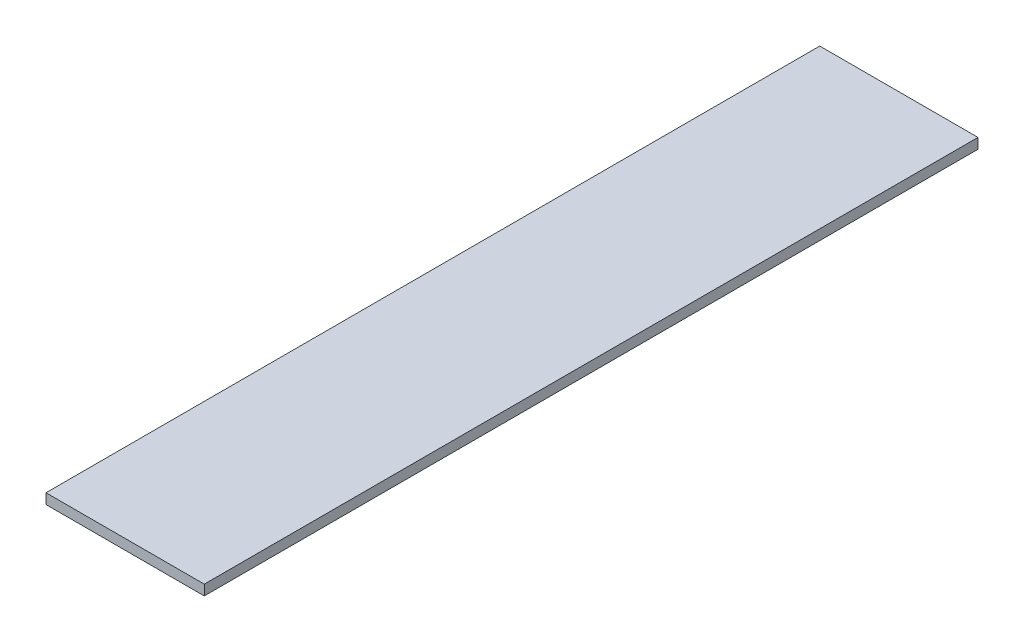
SolidWorks part; units mm, degrees
material "Pine"
ref_plane "Front Plane" through (0, 0, 0) normal (0, 0, 1) x (1, 0, 0)
ref_plane "Top Plane" through (0, 0, 0) normal (0, 1, 0) x (1, 0, 0)
ref_plane "Right Plane" through (0, 0, 0) normal (1, 0, 0) x (0, 0, -1)
sketch "Sketch1" plane through (0, 0, 0) normal (0, 1, 0) x (1, 0, 0)
  line L1 (-42.8625, 209.55) -> (42.8625, 209.55)
  line L2 (-42.8625, 209.55) -> (-42.8625, -209.55)
  line L3 (-42.8625, -209.55) -> (42.8625, -209.55)
  line L4 (42.8625, 209.55) -> (42.8625, -209.55)
  line L5 (-42.8625, 209.55) -> (42.8625, -209.55) construction
  line L6 (-42.8625, -209.55) -> (42.8625, 209.55) construction
  point P0 (0, 0)
  dimension "D1" = 85.725
  dimension "D2" = 419.1
extrude "Boss-Extrude1" add sketch "Sketch1" along normal blind 5.5562
